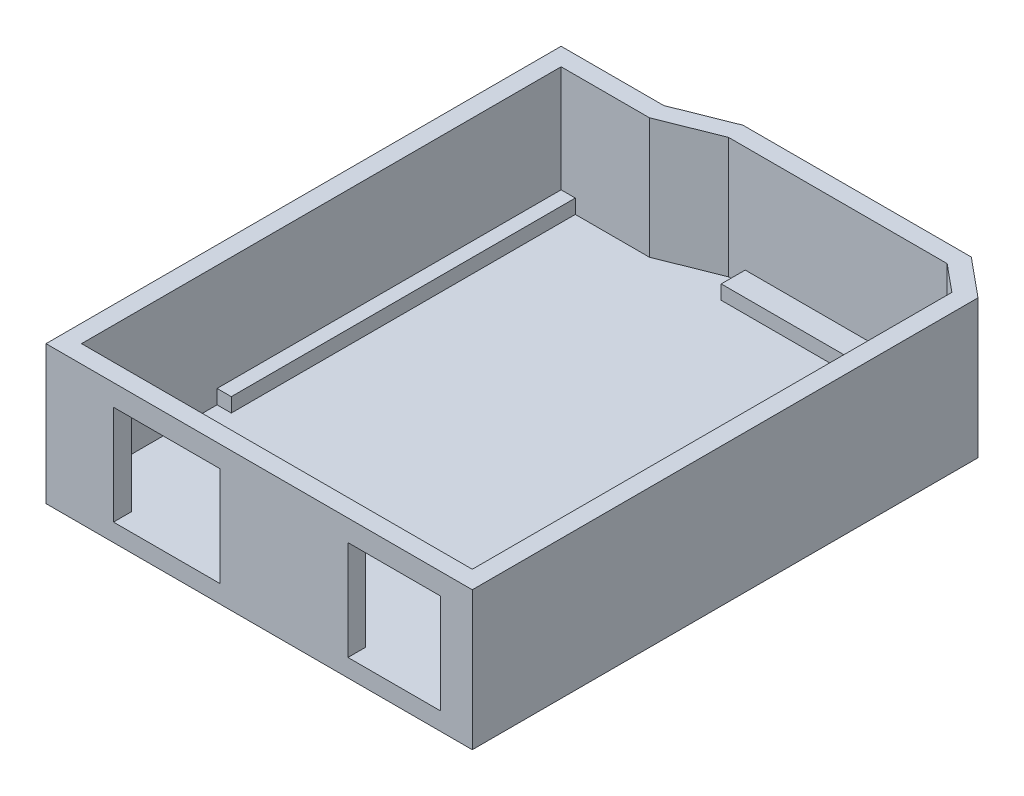
SolidWorks part; units mm, degrees
ref_plane "Front Plane" through (0, 0, 0) normal (0, 0, 1) x (1, 0, 0)
ref_plane "Top Plane" through (0, 0, 0) normal (0, 1, 0) x (1, 0, 0)
ref_plane "Right Plane" through (0, 0, 0) normal (1, 0, 0) x (0, 0, -1)
sketch "Sketch1" plane through (0, 0, 0) normal (0, 1, 0) x (1, 0, 0)
  line L0 (0, 0) -> (0, 67.5)
  line L1 (0, 67.5) -> (12.4337, 67.5)
  line L2 (12.4337, 67.5) -> (20.3928, 70.6768)
  line L3 (20.3928, 70.6768) -> (51.1578, 70.6768)
  line L4 (0, 0) -> (55, 0)
  line L5 (55, 0) -> (55, 67.5)
  line L6 (55, 67.5) -> (51.1578, 70.6768)
  dimension "D1" = 67.5
  dimension "D2" = 55
extrude "Boss-Extrude1" add sketch "Sketch1" along normal blind 17
shell "Shell1" thickness 2.5
sketch "Sketch2" plane through (0, 0, 0) normal (0, 0, -1) x (-1, 0, 0)
  line L0 (2.5, 17) -> (2.5, -2.5) construction
  line L1 (-22, 14) -> (-7, 14)
  line L2 (-22, 14) -> (-22, 0)
  line L3 (-22, 0) -> (-7, 0)
  line L4 (-7, 14) -> (-7, 0)
  line L10 (-57.5, 17) -> (-57.5, -2.5) construction
  line L11 (-40, 14) -> (-53, 14)
  line L12 (-40, 14) -> (-40, 0)
  line L13 (-40, 0) -> (-53, 0)
  line L14 (-53, 14) -> (-53, 0)
  dimension "D1" = 15
  dimension "D2" = 14
  dimension "D3" = 9.5
  dimension "D4" = 4.5
  dimension "D5" = 13
extrude "Cut-Extrude1" cut sketch "Sketch2" against normal blind 4
sketch "Sketch3" plane through (0, 0, 0) normal (0, 1, 0) x (1, 0, 0)
  line L0 (0, 67.5) -> (0, 0) construction
  line L1 (0, 69.0781) -> (2, 69.0781)
  line L2 (0, 69.0781) -> (0, 19.0781)
  line L3 (0, 19.0781) -> (2, 19.0781)
  line L4 (2, 69.0781) -> (2, 19.0781)
  line L5 (27.5, 0) -> (27.5, -11.7567) construction
  line L6 (0, 0) -> (55, 0) construction
  line L7 (55, 69.0781) -> (53, 69.0781)
  line L8 (55, 19.0781) -> (53, 19.0781)
  line L9 (53, 69.0781) -> (53, 19.0781)
  line L10 (55, 69.0781) -> (55, 19.0781)
  dimension "D1" = 2
  dimension "D2" = 50
extrude "Boss-Extrude2" add sketch "Sketch3" along normal blind 2
sketch "Sketch4" plane through (0, 0, 0) normal (0, 1, 0) x (1, 0, 0)
  line L1 (22.7348, 67.3021) -> (48.8818, 67.3021)
  line L2 (22.7348, 67.3021) -> (22.7348, 70.6768)
  line L3 (22.7348, 70.6768) -> (48.8818, 70.6768)
  line L4 (48.8818, 67.3021) -> (48.8818, 70.6768)
  line L5 (51.1578, 70.6768) -> (20.3928, 70.6768) construction
extrude "Boss-Extrude3" add sketch "Sketch4" along normal blind 2
